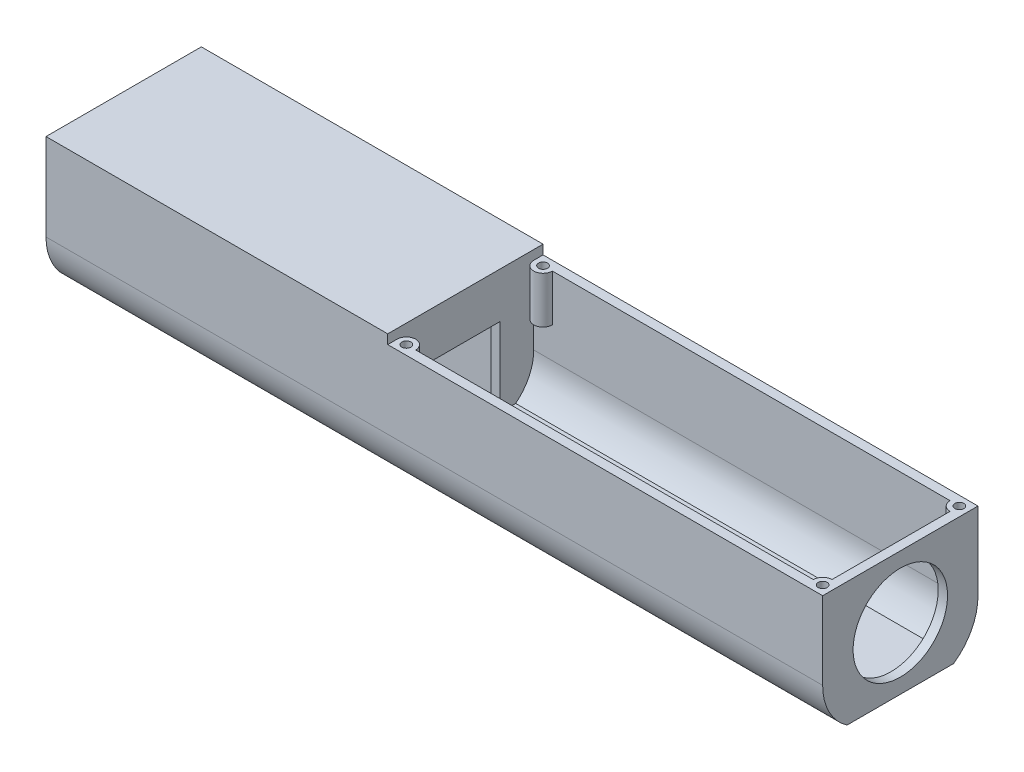
SolidWorks part; units mm, degrees
ref_plane "Front Plane" through (0, 0, 0) normal (0, 0, 1) x (1, 0, 0)
ref_plane "Top Plane" through (0, 0, 0) normal (0, 1, 0) x (1, 0, 0)
ref_plane "Right Plane" through (0, 0, 0) normal (1, 0, 0) x (0, 0, -1)
sketch "Sketch1" plane through (0, 0, 0) normal (1, 0, 0) x (0, 0, -1)
  line L0 (-19.1126, -21.2382) -> (15.2374, -21.2382)
  line L1 (-26.9376, 18.7618) -> (23.0624, 18.7618)
  line L2 (-26.9376, 18.7618) -> (-26.9376, -6.2382)
  line L3 (-26.9376, -6.2382) -> (23.0624, -6.2382)
  line L4 (23.0624, 18.7618) -> (23.0624, -6.2382)
  arc A0 (-26.9376, -6.2382) -> (-19.1126, -21.2382) centre (-8.6481, -6.2382) ccw
  arc A1 (23.0624, -6.2382) -> (15.2374, -21.2382) centre (4.7729, -6.2382) cw
  dimension "D1" = 50
  dimension "D2" = 25
  dimension "D3" = 34.35
  dimension "D4" = 7.825
  dimension "D5" = 40
extrude "Boss-Extrude1" add sketch "Sketch1" along normal blind 250 contours A1 L3 A0 L0 | L4 L1 L2 L3
shell "Shell1" thickness 3
sketch "Sketch2" plane through (0, 0, 0) normal (-1, 0, 0) x (0, 0, 1)
  line L0 (-15.2374, -21.2382) -> (19.1126, -21.2382)
  line L1 (-23.0624, 18.7618) -> (26.9376, 18.7618)
  line L2 (-23.0624, 18.7618) -> (-23.0624, -6.2382)
  line L3 (-23.0624, -6.2382) -> (26.9376, -6.2382)
  line L4 (26.9376, 18.7618) -> (26.9376, -6.2382)
  arc A0 (-23.0624, -6.2382) -> (-15.2374, -21.2382) centre (-4.7729, -6.2382) ccw
  arc A1 (26.9376, -6.2382) -> (19.1126, -21.2382) centre (8.6481, -6.2382) cw
  arc M1 (-23.0624, -6.2382) -> (-15.2374, -21.2382) centre (-4.7729, -6.2382) ccw
  line M2 (-15.2374, -21.2382) -> (19.1126, -21.2382)
  arc M3 (19.1126, -21.2382) -> (26.9376, -6.2382) centre (8.6481, -6.2382) ccw
  line M4 (26.9376, -6.2382) -> (26.9376, 18.7618)
  line M5 (26.9376, 18.7618) -> (-23.0624, 18.7618)
  line M6 (-23.0624, 18.7618) -> (-23.0624, -6.2382)
extrude "Boss-Extrude2" add sketch "Sketch2" against normal blind 110 contours L3 M6 M4 M5 | L3 M1 M2 M3
sketch "Sketch3" plane through (0, 0, 0) normal (-1, 0, 0) x (0, 0, 1)
  line L0 (19.1126, -21.2382) -> (-15.2374, -21.2382) construction
  line L1 (-12.2374, -21.2382) -> (16.1126, -21.2382)
  line L2 (-12.2374, -21.2382) -> (-12.2374, 10.1118)
  line L3 (-12.2374, 10.1118) -> (16.1126, 10.1118)
  line L4 (16.1126, -21.2382) -> (16.1126, 10.1118)
  dimension "D1" = 31.35
  dimension "D2" = 28.35
  dimension "D3" = 3
extrude "Cut-Extrude1" cut sketch "Sketch3" against normal blind 107
sketch "Sketch4" plane through (0, 0, 0) normal (-1, 0, 0) x (0, 0, 1)
  line L1 (-12.2374, 10.1118) -> (16.1126, 10.1118)
  line L2 (-12.2374, 10.1118) -> (-12.2374, 15.1118)
  line L3 (-12.2374, 15.1118) -> (16.1126, 15.1118)
  line L4 (16.1126, 10.1118) -> (16.1126, 15.1118)
  dimension "D1" = 5
extrude "Cut-Extrude2" cut sketch "Sketch4" against normal blind 3
sketch "Sketch5" plane through (3, 0, 0) normal (-1, 0, 0) x (0, 0, 1)
  line L0 (-12.2374, 15.1118) -> (-12.2374, -21.2382) construction
  circle A0 centre (-7.0624, 12.6118) radius 1.45
  circle A1 centre (10.9376, 12.6118) radius 1.45
  dimension "D1" = 2.9
  dimension "D2" = 2.9
  dimension "D3" = 18
  dimension "D4" = 5.175
extrude "Cut-Extrude3" cut sketch "Sketch5" against normal blind 10
sketch "Sketch6" plane through (107, 0, 0) normal (-1, 0, 0) x (0, 0, 1)
  line L0 (-12.2374, -21.2382) -> (16.1126, -21.2382) construction
  line L1 (-2.0624, -20.2382) -> (5.9376, -20.2382)
  line L2 (-2.0624, -20.2382) -> (-2.0624, -18.2382)
  line L3 (-2.0624, -18.2382) -> (5.9376, -18.2382)
  line L4 (5.9376, -20.2382) -> (5.9376, -18.2382)
  point P6 (1.9376, -21.2382)
  dimension "D1" = 4
  dimension "D2" = 3
  dimension "D3" = 2
  dimension "D4" = 8
extrude "Cut-Extrude4" cut sketch "Sketch6" against normal blind 10
sketch "Sketch7" plane through (107, 0, 0) normal (-1, 0, 0) x (0, 0, 1)
  line L0 (16.1126, 10.1118) -> (-12.2374, 10.1118) construction
  line L1 (-9.2374, 7.1118) -> (13.1126, 7.1118)
  line L2 (-9.2374, 7.1118) -> (-9.2374, -16.2382)
  line L3 (-9.2374, -16.2382) -> (13.1126, -16.2382)
  line L4 (13.1126, 7.1118) -> (13.1126, -16.2382)
  line L5 (-12.2374, 10.1118) -> (-12.2374, -21.2382) construction
  line L6 (16.1126, -21.2382) -> (16.1126, 15.1118) construction
  line L7 (5.9376, -18.2382) -> (-2.0624, -18.2382) construction
  dimension "D1" = 3
  dimension "D2" = 3
  dimension "D3" = 3
  dimension "D4" = 2
extrude "Cut-Extrude5" cut sketch "Sketch7" against normal blind 10
sketch "Sketch9" plane through (0, 18.7618, 0) normal (0, 1, 0) x (1, 0, 0)
  line L0 (250, -26.9376) -> (0, -26.9376) construction
  line L1 (0, 23.0624) -> (110, 23.0624)
  line L2 (0, 23.0624) -> (0, -26.9376)
  line L3 (0, -26.9376) -> (110, -26.9376)
  line L4 (110, 23.0624) -> (110, -26.9376)
extrude "Boss-Extrude3" add sketch "Sketch9" along normal blind 3
sketch "Sketch10" plane through (250, 0, 0) normal (1, 0, 0) x (0, 0, -1)
  line L0 (-26.9376, 18.7618) -> (23.0624, 18.7618) construction
  circle A0 centre (-1.9376, -1.2382) radius 15.2
  dimension "D1" = 20
  dimension "D2" = 30.4
extrude "Cut-Extrude6" cut sketch "Sketch10" against normal blind 3
sketch "Sketch11" plane through (0, 18.7618, 0) normal (0, 1, 0) x (1, 0, 0)
  line L0 (247, 20.0624) -> (110, 20.0624) construction
  line L1 (247, -23.9376) -> (110, -23.9376) construction
  line L2 (110, -23.9376) -> (110, -18.1228) construction
  line L3 (110, -26.9376) -> (110, 23.0624) construction
  circle A0 centre (247, -23.9376) radius 3
  circle A1 centre (247, 20.0624) radius 3
  circle A2 centre (113, 20.0624) radius 3
  circle A3 centre (113, -23.9376) radius 3
  dimension "D1" = 3
  dimension "D2" = 3
extrude "Boss-Extrude4" add sketch "Sketch11" against normal blind 15
sketch "Sketch12" plane through (0, 18.7618, 0) normal (0, 1, 0) x (1, 0, 0)
  circle A0 centre (113, 20.0624) radius 1.45
  circle A1 centre (113, -23.9376) radius 1.45
  circle A2 centre (247, -23.9376) radius 1.45
  circle A3 centre (247, 20.0624) radius 1.45
  dimension "D1" = 2.9
  dimension "D2" = 2.9
  dimension "D3" = 2.9
  dimension "D4" = 2.9
extrude "Cut-Extrude7" cut sketch "Sketch12" against normal blind 10
sketch "Sketch13" plane through (0, -18.2382, 0) normal (0, 1, 0) x (1, 0, 0)
  line L1 (247, -18.1228) -> (247, 14.2475) construction
  line L2 (110, -26.9376) -> (110, 23.0624) construction
  circle A0 centre (150, 10.0639) radius 1.6
  circle A1 centre (150, -13.9391) radius 1.6
  circle A2 centre (196.482, -13.9391) radius 1.6
  circle A3 centre (196.482, 10.0639) radius 1.6
  point P12 (247, -1.9376)
  dimension "D1" = 3.2
  dimension "D2" = 3.2
  dimension "D3" = 3.2
  dimension "D4" = 3.2
  dimension "D5" = 46.482
  dimension "D6" = 46.482
  dimension "D7" = 24.003
  dimension "D8" = 12.0015
  dimension "D9" = 40
extrude "Cut-Extrude8" cut sketch "Sketch13" against normal blind 10
chamfer "Chamfer1" distance 1 angle 45 4 edges at (196.482, -21.2382, -8.4639) (196.482, -21.2382, 15.5391) (150, -21.2382, -8.4639) (150, -21.2382, 15.5391)
